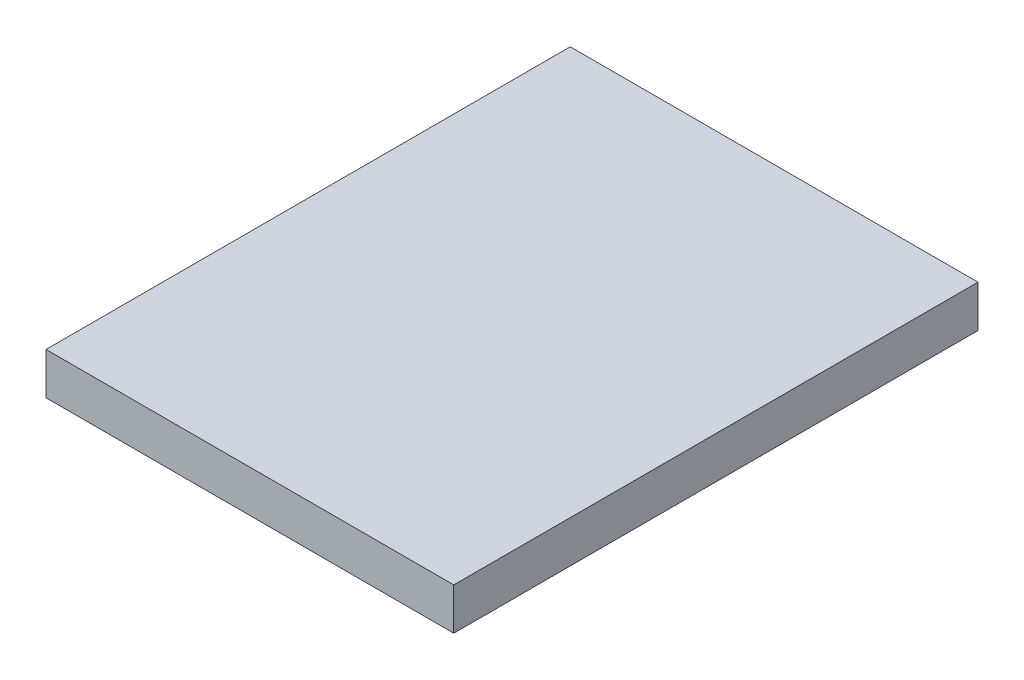
SolidWorks part; units mm, degrees
material "Pine"
ref_plane "Front Plane" through (0, 0, 0) normal (0, 0, 1) x (1, 0, 0)
ref_plane "Top Plane" through (0, 0, 0) normal (0, 1, 0) x (1, 0, 0)
ref_plane "Right Plane" through (0, 0, 0) normal (1, 0, 0) x (0, 0, -1)
sketch "Sketch3" plane through (0, 0, 0) normal (0, 1, 0) x (1, 0, 0)
  line L1 (-88.9, 228.6) -> (88.9, 228.6)
  line L2 (-88.9, 228.6) -> (-88.9, 0)
  line L3 (-88.9, 0) -> (88.9, 0)
  line L4 (88.9, 228.6) -> (88.9, 0)
  point P4 (0, 0)
  dimension "D1" = 228.6
  dimension "D2" = 177.8
extrude "Boss-Extrude1" add sketch "Sketch3" along normal blind 18.2562
